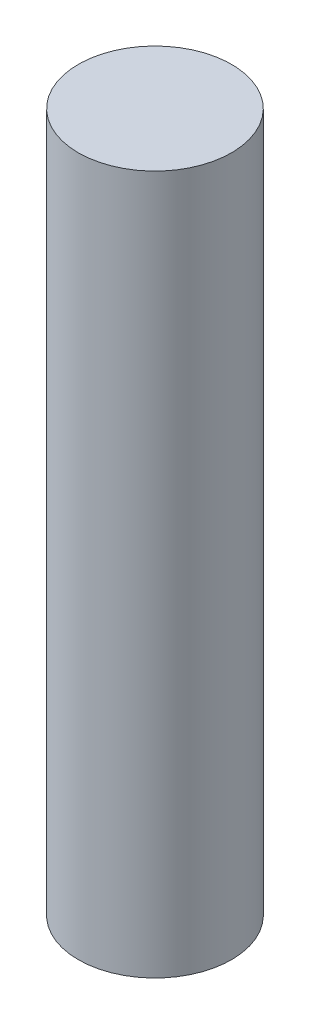
SolidWorks part; units mm, degrees
ref_plane "Front Plane" through (0, 0, 0) normal (0, 0, 1) x (1, 0, 0)
ref_plane "Top Plane" through (0, 0, 0) normal (0, 1, 0) x (1, 0, 0)
ref_plane "Right Plane" through (0, 0, 0) normal (1, 0, 0) x (0, 0, -1)
sketch "Sketch2" plane through (0, 0, 0) normal (0, 1, 0) x (1, 0, 0)
  circle A0 centre (0, 0) radius 50.8
  dimension "D1" = 101.6
extrude "Boss-Extrude1" add sketch "Sketch2" along normal blind 463.296
